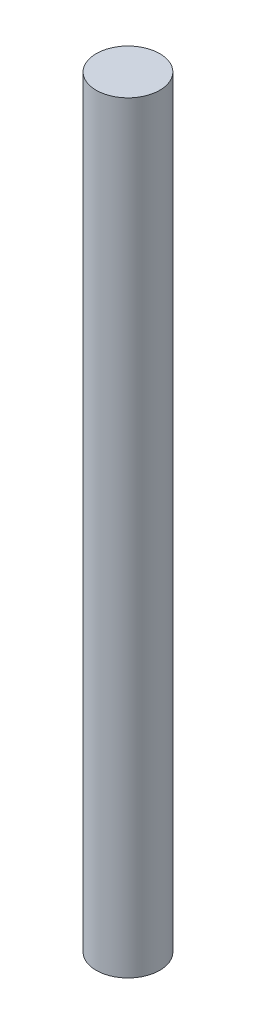
SolidWorks part; units mm, degrees
ref_plane "Front Plane" through (0, 0, 0) normal (0, 0, 1) x (1, 0, 0)
ref_plane "Top Plane" through (0, 0, 0) normal (0, 1, 0) x (1, 0, 0)
ref_plane "Right Plane" through (0, 0, 0) normal (1, 0, 0) x (0, 0, -1)
sketch "Sketch1" plane through (0, 0, 0) normal (0, 1, 0) x (1, 0, 0)
  circle A0 centre (0, 0) radius 4
  dimension "D1" = 8
extrude "Boss-Extrude1" add sketch "Sketch1" along normal blind 96
